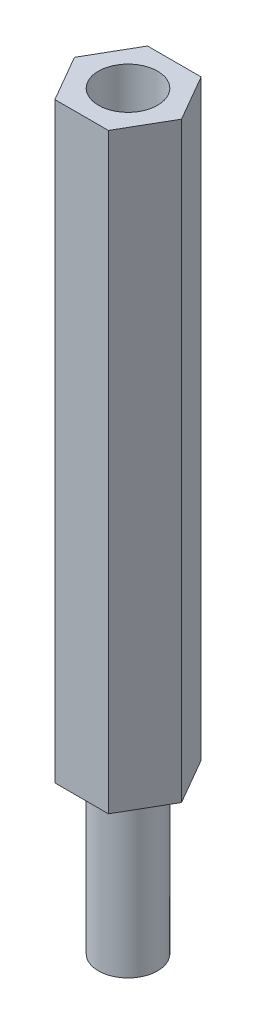
SolidWorks part; units mm, degrees
material "黄铜"
ref_plane "前视基准面" through (0, 0, 0) normal (0, 0, 1) x (1, 0, 0)
ref_plane "上视基准面" through (0, 0, 0) normal (0, 1, 0) x (1, 0, 0)
ref_plane "右视基准面" through (0, 0, 0) normal (1, 0, 0) x (0, 0, -1)
sketch "草图1" plane through (0, 0, 0) normal (0, 1, 0) x (1, 0, 0)
  line L1 (2.7135, 0) -> (1.3568, 2.35)
  line L2 (1.3568, 2.35) -> (-1.3568, 2.35)
  line L3 (-1.3568, 2.35) -> (-2.7135, 0)
  line L4 (-2.7135, 0) -> (-1.3568, -2.35)
  line L5 (-1.3568, -2.35) -> (1.3568, -2.35)
  line L6 (1.3568, -2.35) -> (2.7135, 0)
  circle A0 centre (0, 0) radius 1.5
  circle A1 centre (0, 0) radius 2.35 construction
  dimension "D1" = 3
  dimension "D2" = 4.7
extrude "凸台-拉伸1" add sketch "草图1" along normal blind 30
sketch "草图2" plane through (0, 0, 0) normal (0, -1, 0) x (-1, 0, 0)
  circle A0 centre (0, 0) radius 1.5
extrude "凸台-拉伸2" add sketch "草图2" along normal blind 8 separate body
